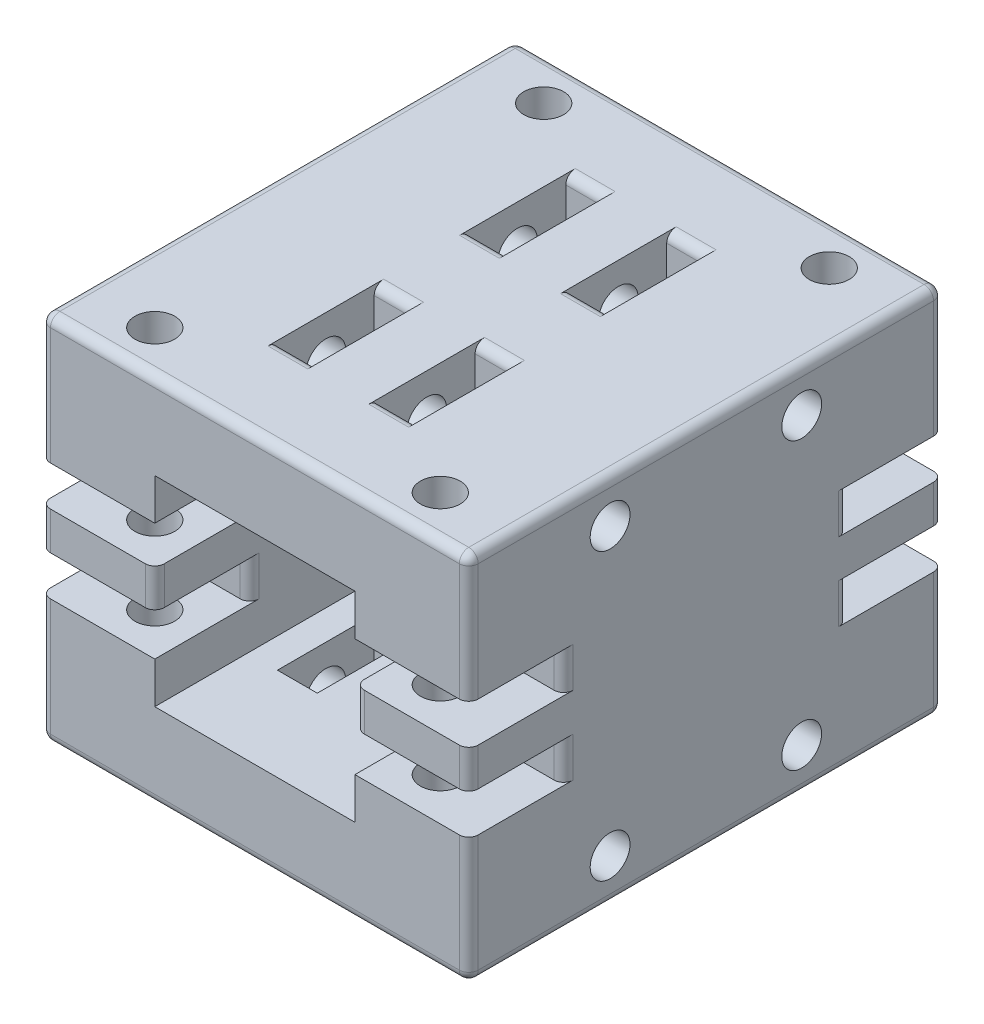
SolidWorks part; units mm, degrees
ref_plane "前视基准面" through (0, 0, 0) normal (0, 0, 1) x (1, 0, 0)
ref_plane "上视基准面" through (0, 0, 0) normal (0, 1, 0) x (1, 0, 0)
ref_plane "右视基准面" through (0, 0, 0) normal (1, 0, 0) x (0, 0, -1)
other "Configuration Table"
sketch "草图1" plane through (0, 0, 0) normal (0, 0, 1) x (1, 0, 0)
  line L1 (0, 0) -> (21.1, 0)
  line L2 (0, 0) -> (0, 21.1)
  line L3 (0, 21.1) -> (21.1, 21.1)
  line L4 (21.1, 0) -> (21.1, 21.1)
  line L5 (-12, -9) -> (33.1, -9)
  line L6 (-12, -9) -> (-12, 30.1)
  line L7 (-12, 30.1) -> (33.1, 30.1)
  line L8 (33.1, -9) -> (33.1, 30.1)
  dimension "D1" = 21.1
  dimension "D2" = 21.1
  dimension "D3" = 9
  dimension "D4" = 12
  dimension "D5" = 12
  dimension "D6" = 9
extrude "凸台-拉伸1" add sketch "草图1" along normal blind 50
sketch "草图2" plane through (0, 0, 50) normal (0, 0, 1) x (1, 0, 0)
  line L0 (21.1, 0) -> (21.1, 21.1) construction
  line L1 (21.1, 16.75) -> (33.1, 16.75)
  line L2 (21.1, 16.75) -> (21.1, 12.55)
  line L3 (21.1, 12.55) -> (33.1, 12.55)
  line L4 (33.1, 16.75) -> (33.1, 12.55)
  line L5 (33.1, -9) -> (33.1, 30.1) construction
  line L6 (10.55, 20.2) -> (10.55, 0) construction
  line L7 (21.1, 8.55) -> (33.1, 8.55)
  line L8 (21.1, 8.55) -> (21.1, 4.35)
  line L9 (21.1, 4.35) -> (33.1, 4.35)
  line L10 (33.1, 8.55) -> (33.1, 4.35)
  line L13 (0, 21.1) -> (21.1, 21.1) construction
  line L14 (0, 4.35) -> (-12, 4.35)
  line L15 (-12, 8.55) -> (-12, 4.35)
  line L16 (0, 8.55) -> (-12, 8.55)
  line L17 (0, 8.55) -> (0, 4.35)
  line L18 (0, 12.55) -> (-12, 12.55)
  line L19 (-12, 16.75) -> (-12, 12.55)
  line L20 (0, 16.75) -> (-12, 16.75)
  line L21 (0, 16.75) -> (0, 12.55)
  line L22 (0, 21.1) -> (0, 0) construction
  line L23 (-13.7854, 10.55) -> (32.4942, 10.55) construction
  point P15 (10.55, 21.1)
  point P31 (0, 10.55)
  dimension "D1" = 4.2
  dimension "D2" = 4.2
  dimension "D3" = 4
extrude "切除-拉伸1" cut sketch "草图2" against normal blind 10
sketch "草图3" plane through (0, 12.55, 0) normal (0, 1, 0) x (1, 0, 0)
  line L0 (10.55, 9.0659) -> (10.55, -45.9792) construction
  line L1 (-12, 0) -> (33.1, 0) construction
  line L4 (21.1, -50) -> (33.1, -50)
  line L5 (33.1, -50) -> (33.1, -40)
  line L6 (33.1, -40) -> (21.1, -40)
  line L7 (21.1, -40) -> (21.1, -50)
  line L8 (21.1, -50) -> (33.1, -50) construction
  line L9 (33.1, -50) -> (33.1, -40) construction
  line L10 (33.1, -40) -> (21.1, -40) construction
  line L11 (21.1, -40) -> (21.1, -50) construction
  circle A0 centre (25.6, -45.5) radius 2.1
  circle A1 centre (-4.5, -45.5) radius 2.1
  point P10 (10.55, 0)
  dimension "D2" = 4.2
  dimension "D3" = 4.5
  dimension "D4" = 5.5
  dimension "D1" = 0
extrude "切除-拉伸2" cut sketch "草图3" against normal blind 30 and the other way blind 30
sketch "草图4" plane through (0, 0, 0) normal (0, 0, -1) x (-1, 0, 0)
  line L0 (0, 4.35) -> (0, 8.55) construction
  line L1 (0, 8.55) -> (12, 8.55) construction
  line L2 (12, 8.55) -> (12, 4.35) construction
  line L3 (12, 4.35) -> (0, 4.35) construction
  line L4 (0, 12.55) -> (0, 16.75) construction
  line L5 (0, 16.75) -> (12, 16.75) construction
  line L6 (12, 16.75) -> (12, 12.55) construction
  line L7 (12, 12.55) -> (0, 12.55) construction
  line L8 (-21.1, 8.55) -> (-21.1, 4.35) construction
  line L9 (-21.1, 4.35) -> (-33.1, 4.35) construction
  line L10 (-33.1, 4.35) -> (-33.1, 8.55) construction
  line L11 (-33.1, 8.55) -> (-21.1, 8.55) construction
  line L12 (-21.1, 16.75) -> (-21.1, 12.55) construction
  line L13 (-21.1, 12.55) -> (-33.1, 12.55) construction
  line L14 (-33.1, 12.55) -> (-33.1, 16.75) construction
  line L15 (-33.1, 16.75) -> (-21.1, 16.75) construction
  line L16 (0, 4.35) -> (0, 8.55)
  line L17 (0, 8.55) -> (12, 8.55)
  line L18 (12, 8.55) -> (12, 4.35)
  line L19 (12, 4.35) -> (0, 4.35)
  line L20 (0, 12.55) -> (0, 16.75)
  line L21 (0, 16.75) -> (12, 16.75)
  line L22 (12, 16.75) -> (12, 12.55)
  line L23 (12, 12.55) -> (0, 12.55)
  line L24 (-21.1, 8.55) -> (-21.1, 4.35)
  line L25 (-21.1, 4.35) -> (-33.1, 4.35)
  line L26 (-33.1, 4.35) -> (-33.1, 8.55)
  line L27 (-33.1, 8.55) -> (-21.1, 8.55)
  line L28 (-21.1, 16.75) -> (-21.1, 12.55)
  line L29 (-21.1, 12.55) -> (-33.1, 12.55)
  line L30 (-33.1, 12.55) -> (-33.1, 16.75)
  line L31 (-33.1, 16.75) -> (-21.1, 16.75)
extrude "切除-拉伸3" cut sketch "草图4" against normal blind 10
sketch "草图5" plane through (0, 12.55, 0) normal (0, 1, 0) x (1, 0, 0)
  line L0 (10.55, 8.0486) -> (10.55, -10) construction
  line L1 (-12, 0) -> (33.1, 0) construction
  line L4 (33.1, 0) -> (21.1, 0)
  line L5 (21.1, 0) -> (21.1, -10)
  line L6 (21.1, -10) -> (33.1, -10)
  line L7 (33.1, -10) -> (33.1, 0)
  line L8 (33.1, 0) -> (21.1, 0) construction
  line L9 (21.1, 0) -> (21.1, -10) construction
  line L10 (21.1, -10) -> (33.1, -10) construction
  line L11 (33.1, -10) -> (33.1, 0) construction
  circle A0 centre (25.6, -4.5) radius 2.1
  circle A1 centre (-4.5, -4.5) radius 2.1
  point P9 (10.55, 0)
  dimension "D2" = 4.2
  dimension "D3" = 4.5
  dimension "D4" = 5.5
  dimension "D1" = 0
extrude "切除-拉伸4" cut sketch "草图5" against normal blind 30 and the other way blind 30
sketch "草图6" plane through (0, 30.1, 0) normal (0, 1, 0) x (1, 0, 0)
  line L0 (-12, 0) -> (33.1, 0) construction
  line L1 (10.55, 6.2804) -> (10.55, -54.2395) construction
  line L2 (-32.8056, -25) -> (52.8172, -25) construction
  line L3 (13.7689, -9.8) -> (17.9689, -9.8)
  line L4 (13.7689, -9.8) -> (13.7689, -20)
  line L5 (13.7689, -20) -> (17.9689, -20)
  line L6 (17.9689, -9.8) -> (17.9689, -20)
  line L11 (33.1, 0) -> (33.1, -50) construction
  line L12 (7.3311, -20) -> (3.1311, -20)
  line L13 (3.1311, -9.8) -> (3.1311, -20)
  line L14 (7.3311, -9.8) -> (3.1311, -9.8)
  line L15 (7.3311, -9.8) -> (7.3311, -20)
  line L16 (7.3311, -40.2) -> (7.3311, -30)
  line L17 (7.3311, -40.2) -> (3.1311, -40.2)
  line L18 (3.1311, -40.2) -> (3.1311, -30)
  line L19 (7.3311, -30) -> (3.1311, -30)
  line L20 (13.7689, -30) -> (17.9689, -30)
  line L21 (17.9689, -40.2) -> (17.9689, -30)
  line L22 (13.7689, -40.2) -> (17.9689, -40.2)
  line L23 (13.7689, -40.2) -> (13.7689, -30)
  point P6 (10.55, 0)
  point P17 (33.1, -25)
  dimension "D1" = 4.2
  dimension "D2" = 10.2
  dimension "D3" = 10
extrude "切除-拉伸5" cut sketch "草图6" against normal blind 80
sketch "草图7" plane through (13.7689, 0, 0) normal (1, 0, 0) x (0, 0, -1)
  line L0 (-9.8, -9) -> (-9.8, 0) construction
  line L1 (-9.8, 0) -> (-20, 0) construction
  line L2 (-20, 0) -> (-20, -9) construction
  line L3 (-20, -9) -> (-9.8, -9) construction
  line L4 (-30, -9) -> (-30, 0) construction
  line L5 (-30, 0) -> (-40.2, 0) construction
  line L6 (-40.2, 0) -> (-40.2, -9) construction
  line L7 (-40.2, -9) -> (-30, -9) construction
  line L8 (-20, 21.1) -> (-9.8, 21.1) construction
  line L9 (-9.8, 21.1) -> (-9.8, 30.1) construction
  line L10 (-9.8, 30.1) -> (-20, 30.1) construction
  line L11 (-20, 30.1) -> (-20, 21.1) construction
  line L12 (-40.2, 21.1) -> (-30, 21.1) construction
  line L13 (-30, 21.1) -> (-30, 30.1) construction
  line L14 (-30, 30.1) -> (-40.2, 30.1) construction
  line L15 (-40.2, 30.1) -> (-40.2, 21.1) construction
  line L16 (-9.8, -9) -> (-9.8, 0) construction
  line L17 (-9.8, 0) -> (-20, 0) construction
  line L18 (-20, 0) -> (-20, -9) construction
  line L19 (-20, -9) -> (-9.8, -9) construction
  line L20 (-30, -9) -> (-30, 0) construction
  line L21 (-30, 0) -> (-40.2, 0) construction
  line L22 (-40.2, 0) -> (-40.2, -9) construction
  line L23 (-40.2, -9) -> (-30, -9) construction
  line L24 (-20, 21.1) -> (-9.8, 21.1) construction
  line L25 (-9.8, 21.1) -> (-9.8, 30.1) construction
  line L26 (-9.8, 30.1) -> (-20, 30.1) construction
  line L27 (-20, 30.1) -> (-20, 21.1) construction
  line L28 (-40.2, 21.1) -> (-30, 21.1) construction
  line L29 (-30, 21.1) -> (-30, 30.1) construction
  line L30 (-30, 30.1) -> (-40.2, 30.1) construction
  line L31 (-40.2, 30.1) -> (-40.2, 21.1) construction
  line L32 (-50, 10.55) -> (0, 10.55) construction
  line L33 (-50, 8.55) -> (-50, 12.55) construction
  line L34 (0, 8.55) -> (0, 12.55) construction
  line L35 (-25, 30.1) -> (-25, -9) construction
  line L36 (-50, 30.1) -> (0, 30.1) construction
  line L37 (-50, -9) -> (0, -9) construction
  circle A0 centre (-35.1, 25.6) radius 2.1
  circle A1 centre (-14.9, 25.6) radius 2.1
  circle A2 centre (-14.9, -4.5) radius 2.1
  circle A3 centre (-35.1, -4.5) radius 2.1
  point P30 (-35.1, 30.1)
  dimension "D1" = 4.2
  dimension "D2" = 4.5
extrude "切除-拉伸6" cut sketch "草图7" against normal blind 80 and the other way blind 80
fillet "圆角1" radius 1 56 edges at (10.55, -9, 0) (33.1, 30.1, 25) (33.1, 23.425, 50) (10.55, 30.1, 50) (10.55, -9, 50) (33.1, -2.325, 50) (-12, -2.325, 50) (-12, 23.425, 50) (-12, 30.1, 25) (10.55, 30.1, 0) (33.1, 23.425, 0) (33.1, -2.325, 0) (-12, -2.325, 0) (-12, 23.425, 0) (33.1, -9, 25) (-12, -9, 25) (33.1, 14.65, 10) (33.1, 6.45, 10) (33.1, 6.45, 40) (33.1, 14.65, 40) (21.1, 14.65, 10) (21.1, 6.45, 10) (21.1, 6.45, 40) (21.1, 14.65, 40) (0, 14.65, 40) (0, 6.45, 40) (0, 6.45, 10) (0, 14.65, 10) (-12, 14.65, 10) (-12, 6.45, 10) (-12, 6.45, 40) (-12, 14.65, 40) (0, 10.55, 0) (-12, 10.55, 0) (21.1, 10.55, 0) (33.1, 10.55, 0) (-12, 10.55, 50) (21.1, 10.55, 50) (0, 10.55, 50) (33.1, 10.55, 50) (15.8689, -9, 40.2) (15.8689, -9, 30) (5.2311, -9, 40.2) (5.2311, -9, 30) (15.8689, -9, 9.8) (15.8689, -9, 20) (5.2311, -9, 20) (5.2311, -9, 9.8) (5.2311, 30.1, 40.2) (5.2311, 30.1, 30) (15.8689, 30.1, 40.2) (15.8689, 30.1, 30) (15.8689, 30.1, 20) (15.8689, 30.1, 9.8) (5.2311, 30.1, 20) (5.2311, 30.1, 9.8)
